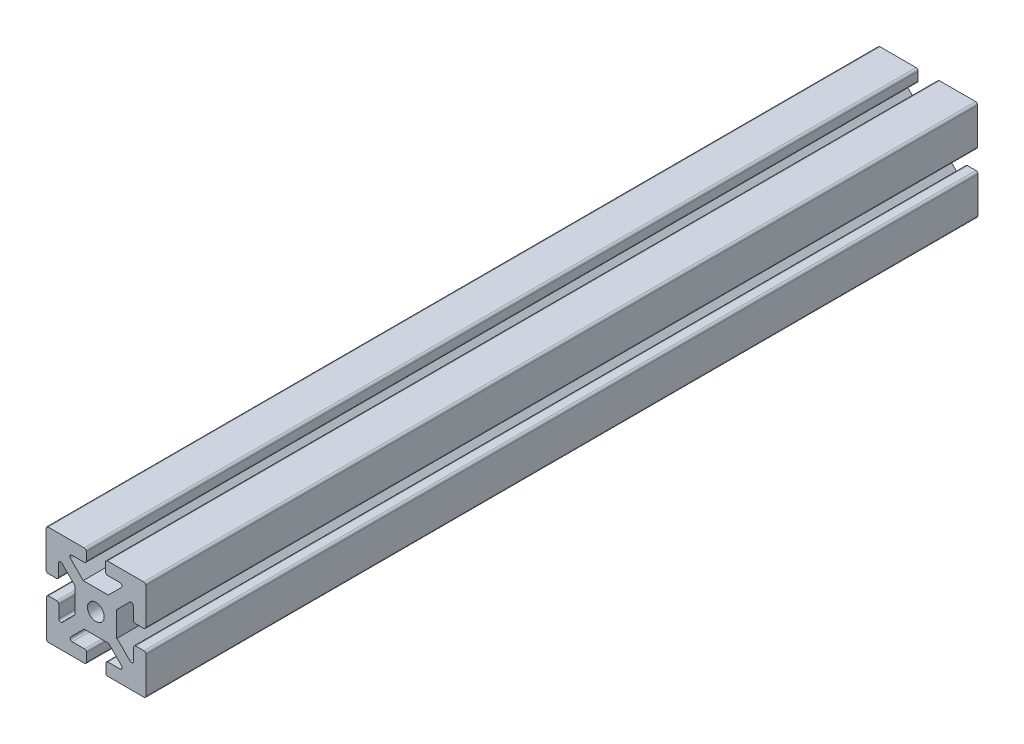
SolidWorks part; units mm, degrees
material "6061-T4 (SS)"
ref_plane "Front Plane" through (0, 0, 0) normal (0, 0, 1) x (1, 0, 0)
ref_plane "Top Plane" through (0, 0, 0) normal (0, 1, 0) x (1, 0, 0)
ref_plane "Right Plane" through (0, 0, 0) normal (1, 0, 0) x (0, 0, -1)
sketch "Sketch1" plane through (0, 0, 0) normal (0, 0, 1) x (1, 0, 0)
  line L0 (429.2666, -288.9781) -> (440.6347, -288.9781)
  line L1 (-3070.7334, 2211.0219) -> (1929.2666, 2211.0219)
  line L2 (-3070.7334, 2211.0219) -> (-3070.7334, -2788.9781)
  line L3 (-3070.7334, -2788.9781) -> (1929.2666, -2788.9781)
  line L4 (1929.2666, 2211.0219) -> (1929.2666, -2788.9781)
  line L5 (-3070.7334, 2211.0219) -> (1929.2666, -2788.9781) construction
  line L6 (-3070.7334, -2788.9781) -> (-570.7334, -288.9781) construction
  line L7 (5429.2666, 1120.7706) -> (5429.2666, 5461.0219)
  line L9 (4179.2666, 870.7706) -> (5179.2666, 870.7706)
  line L10 (3502.4899, 2772.8771) -> (1929.2666, 1199.6538)
  line L11 (839.0153, 4211.0219) -> (2314.3452, 4211.0219)
  line L12 (917.8986, 2211.0219) -> (1929.2666, 1199.6538)
  line L13 (1966.6284, -1769.9381) -> (955.2604, -2781.3062)
  line L14 (3929.2666, 1120.7706) -> (3929.2666, 2596.1004)
  line L15 (2491.1219, 3784.2452) -> (917.8986, 2211.0219)
  line L16 (589.0153, 4461.0219) -> (589.0153, 5461.0219)
  line L17 (839.0153, 5711.0219) -> (5179.2666, 5711.0219)
  line L18 (1929.2666, 2211.0219) -> (-3070.7334, 2211.0219)
  line L19 (1929.2666, -2788.9781) -> (1929.2666, 2211.0219)
  line L20 (2528.4837, -4354.5295) -> (955.2604, -2781.3062)
  line L21 (876.3771, -4781.3062) -> (2351.707, -4781.3062)
  line L22 (626.3771, -5031.3062) -> (626.3771, -6031.3062)
  line L23 (876.3771, -6281.3062) -> (5216.6284, -6281.3062)
  line L24 (5466.6284, -1691.0549) -> (5466.6284, -6031.3062)
  line L25 (4216.6284, -1441.0549) -> (5216.6284, -1441.0549)
  line L26 (3966.6284, -1691.0549) -> (3966.6284, -3166.3847)
  line L27 (3539.8517, -3343.1614) -> (1966.6284, -1769.9381)
  line L28 (-2014.3316, -2818.668) -> (-3025.6996, -1807.2999)
  line L29 (-4598.9229, -3380.5232) -> (-3025.6996, -1807.2999)
  line L30 (-5025.6996, -1728.4167) -> (-5025.6996, -3203.7465)
  line L31 (-5275.6996, -1478.4167) -> (-6275.6996, -1478.4167)
  line L32 (-6525.6996, -1728.4167) -> (-6525.6996, -6068.668)
  line L33 (-1935.4484, -6318.668) -> (-6275.6996, -6318.668)
  line L34 (-1685.4484, -5068.668) -> (-1685.4484, -6068.668)
  line L35 (-1935.4484, -4818.668) -> (-3410.7782, -4818.668)
  line L36 (-3587.5549, -4391.8913) -> (-2014.3316, -2818.668)
  line L37 (-3063.0614, 1162.292) -> (-2051.6934, 2173.6601)
  line L38 (-3624.9167, 3746.8834) -> (-2051.6934, 2173.6601)
  line L39 (-1972.8101, 4173.6601) -> (-3448.14, 4173.6601)
  line L40 (-1722.8101, 4423.6601) -> (-1722.8101, 5423.6601)
  line L41 (-1972.8101, 5673.6601) -> (-6313.0614, 5673.6601)
  line L42 (-6563.0614, 1083.4088) -> (-6563.0614, 5423.6601)
  line L43 (-5313.0614, 833.4088) -> (-6313.0614, 833.4088)
  line L44 (-5063.0614, 1083.4088) -> (-5063.0614, 2558.7386)
  line L45 (-4636.2847, 2735.5153) -> (-3063.0614, 1162.292)
  circle A0 centre (-570.7334, -288.9781) radius 1000
  arc A1 (2314.3452, 4211.0219) -> (2491.1219, 3784.2452) centre (2314.3452, 3961.0219) cw
  arc A2 (3929.2666, 2596.1004) -> (3502.4899, 2772.8771) centre (3679.2666, 2596.1004) ccw
  arc A3 (589.0153, 5461.0219) -> (839.0153, 5711.0219) centre (839.0153, 5461.0219) cw
  arc A4 (839.0153, 4211.0219) -> (589.0153, 4461.0219) centre (839.0153, 4461.0219) cw
  arc A5 (3929.2666, 1120.7706) -> (4179.2666, 870.7706) centre (4179.2666, 1120.7706) ccw
  arc A6 (5179.2666, 870.7706) -> (5429.2666, 1120.7706) centre (5179.2666, 1120.7706) ccw
  arc A7 (5429.2666, 5461.0219) -> (5179.2666, 5711.0219) centre (5179.2666, 5461.0219) ccw
  arc A10 (2351.707, -4781.3062) -> (2528.4837, -4354.5295) centre (2351.707, -4531.3062) ccw
  arc A11 (876.3771, -4781.3062) -> (626.3771, -5031.3062) centre (876.3771, -5031.3062) ccw
  arc A12 (626.3771, -6031.3062) -> (876.3771, -6281.3062) centre (876.3771, -6031.3062) ccw
  arc A13 (5216.6284, -6281.3062) -> (5466.6284, -6031.3062) centre (5216.6284, -6031.3062) ccw
  arc A14 (5216.6284, -1441.0549) -> (5466.6284, -1691.0549) centre (5216.6284, -1691.0549) cw
  arc A15 (3966.6284, -1691.0549) -> (4216.6284, -1441.0549) centre (4216.6284, -1691.0549) cw
  arc A16 (3966.6284, -3166.3847) -> (3539.8517, -3343.1614) centre (3716.6284, -3166.3847) cw
  arc A17 (-5025.6996, -3203.7465) -> (-4598.9229, -3380.5232) centre (-4775.6996, -3203.7465) ccw
  arc A18 (-5025.6996, -1728.4167) -> (-5275.6996, -1478.4167) centre (-5275.6996, -1728.4167) ccw
  arc A19 (-6275.6996, -1478.4167) -> (-6525.6996, -1728.4167) centre (-6275.6996, -1728.4167) ccw
  arc A20 (-6525.6996, -6068.668) -> (-6275.6996, -6318.668) centre (-6275.6996, -6068.668) ccw
  arc A21 (-1685.4484, -6068.668) -> (-1935.4484, -6318.668) centre (-1935.4484, -6068.668) cw
  arc A22 (-1935.4484, -4818.668) -> (-1685.4484, -5068.668) centre (-1935.4484, -5068.668) cw
  arc A23 (-3410.7782, -4818.668) -> (-3587.5549, -4391.8913) centre (-3410.7782, -4568.668) cw
  arc A24 (-3448.14, 4173.6601) -> (-3624.9167, 3746.8834) centre (-3448.14, 3923.6601) ccw
  arc A25 (-1972.8101, 4173.6601) -> (-1722.8101, 4423.6601) centre (-1972.8101, 4423.6601) ccw
  arc A26 (-1722.8101, 5423.6601) -> (-1972.8101, 5673.6601) centre (-1972.8101, 5423.6601) ccw
  arc A27 (-6313.0614, 5673.6601) -> (-6563.0614, 5423.6601) centre (-6313.0614, 5423.6601) ccw
  arc A28 (-6313.0614, 833.4088) -> (-6563.0614, 1083.4088) centre (-6313.0614, 1083.4088) cw
  arc A29 (-5063.0614, 1083.4088) -> (-5313.0614, 833.4088) centre (-5313.0614, 1083.4088) cw
  arc A30 (-5063.0614, 2558.7386) -> (-4636.2847, 2735.5153) centre (-4813.0614, 2558.7386) cw
  point P105 (-548.2165, -303.823)
  dimension "D1" = 250
  dimension "D2" = 4
sketch "Sketch2" plane through (0, 0, 0) normal (0, 0, 1) x (1, 0, 0)
extrude "Boss-Extrude1" add sketch "Sketch1" along normal blind 100000 contours L37 L38 A24 L39 A25 L40 A26 L41 A27 L42 A28 L43 A29 L44 A30 L45 | L12 L10 A2 L14 A5 L9 A6 L7 A7 L17 A3 L16 A4 L11 A1 L15 | L13 L20 A10 L21 A11 L22 A12 L23 A13 L24 A14 L25 A15 L26 A16 L27 | L28 L29 A17 L30 A18 L31 A19 L32 A20 L33 A21 L34 A22 L35 A23 L36 | L2 L1 L4 L3 | A0
